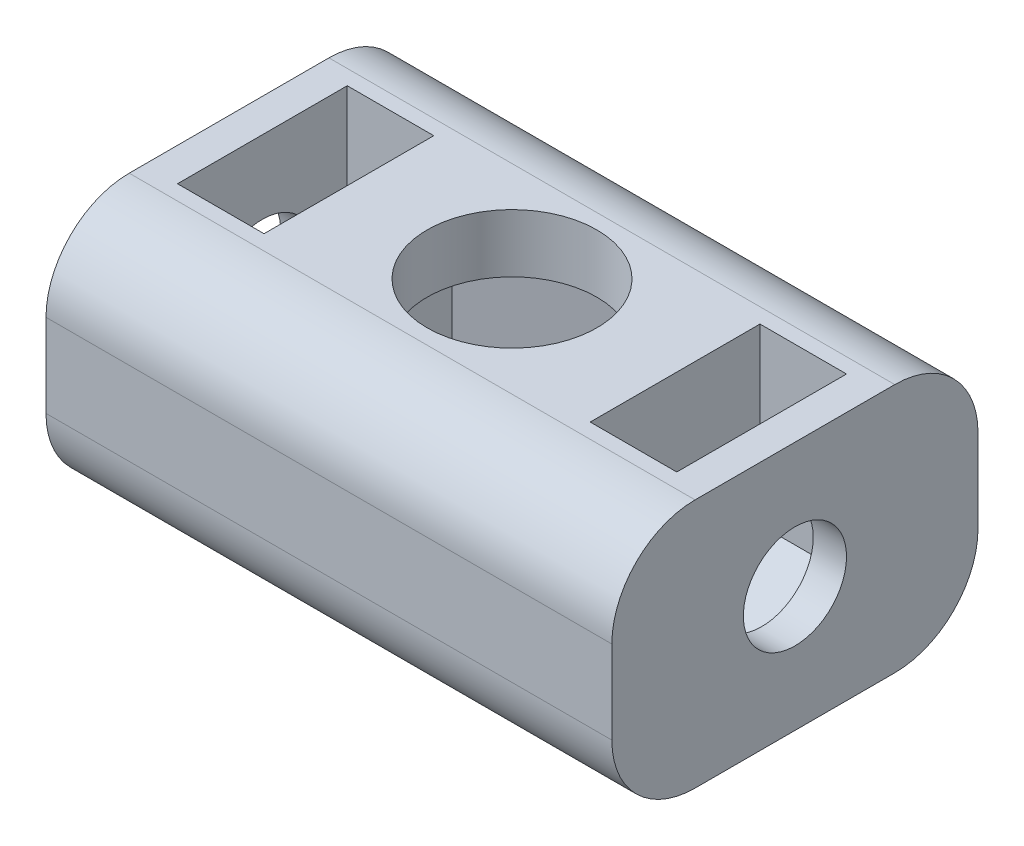
SolidWorks part; units mm, degrees
ref_plane "Alzado" through (0, 0, 0) normal (0, 0, 1) x (1, 0, 0)
ref_plane "Planta" through (0, 0, 0) normal (0, 1, 0) x (1, 0, 0)
ref_plane "Vista lateral" through (0, 0, 0) normal (1, 0, 0) x (0, 0, -1)
sketch "Croquis1" plane through (0, 0, 0) normal (0, 1, 0) x (1, 0, 0)
  line L0 (17, 22) -> (17, 0) construction
  line L1 (0, 0) -> (34, 0)
  line L2 (0, 0) -> (0, 22)
  line L3 (0, 22) -> (34, 22)
  line L4 (34, 0) -> (34, 22)
  circle A0 centre (17, 11) radius 5.1
  dimension "D3" = 10.2
  dimension "D1" = 34
  dimension "D2" = 22
extrude "Saliente-Extruir1" add sketch "Croquis1" along normal blind 15
ref_plane "Plano1" through (2, 0, 0) normal (-1, 0, 0) x (0, 0, 1)
sketch "Croquis2" plane through (2, 0, 0) normal (-1, 0, 0) x (0, 0, 1)
  line L0 (-11, 15) -> (-11, 0) construction
  line L1 (-22, 15) -> (0, 15) construction
  line L2 (-22, 0) -> (0, 0) construction
  line L3 (-16.1, 10.4445) -> (-16.1, 15)
  line L4 (-11, 1.611) -> (-5.9, 4.5555)
  line L5 (-5.9, 4.5555) -> (-5.9, 10.4445)
  line L6 (-5.9, 10.4445) -> (-11, 13.389) construction
  line L7 (-11, 13.389) -> (-16.1, 10.4445) construction
  line L8 (-16.1, 10.4445) -> (-16.1, 4.5555)
  line L9 (-16.1, 4.5555) -> (-11, 1.611)
  line L10 (-16.1, 15) -> (-5.9, 15)
  line L11 (-5.9, 15) -> (-5.9, 10.4445)
  circle A0 centre (-11, 7.5) radius 5.1 construction
  point P7 (-16.1, 7.5)
  point P15 (0, 0)
  point P20 (-19.6485, 15)
  dimension "D1" = 10.2
extrude "Cortar-Extruir1" cut sketch "Croquis2" against normal blind 5.2
ref_plane "Plano2" through (32, 0, 0) normal (1, 0, 0) x (0, 0, -1)
sketch "Croquis3" plane through (32, 0, 0) normal (1, 0, 0) x (0, 0, -1)
  line L0 (5.9, 15) -> (5.9, 0) construction
  line L1 (16.1, 0) -> (16.1, 15) construction
  line L2 (0, 15) -> (22, 15) construction
  line L3 (16.1, 4.5555) -> (11, 1.611) construction
  line L4 (11, 1.611) -> (5.9, 4.5555) construction
  line L5 (5.9, 15) -> (5.9, 4.5555)
  line L6 (16.1, 4.5555) -> (16.1, 15)
  line L7 (5.9, 15) -> (16.1, 15)
  line L8 (16.1, 4.5555) -> (11, 1.611)
  line L9 (11, 1.611) -> (5.9, 4.5555)
extrude "Cortar-Extruir2" cut sketch "Croquis3" against normal blind 5.2
ref_plane "Plano3" through (0, 7.5, 0) normal (0, 1, 0) x (1, 0, 0)
sketch "Croquis4" plane through (0, 7.5, 0) normal (0, 1, 0) x (1, 0, 0)
  line L0 (17, 20.815) -> (17, 22) construction
  line L1 (8.5, 6.0925) -> (17, 1.185)
  line L2 (17, 1.185) -> (25.5, 6.0925)
  line L3 (25.5, 6.0925) -> (25.5, 15.9075)
  line L4 (25.5, 15.9075) -> (17, 20.815)
  line L5 (17, 20.815) -> (8.5, 15.9075)
  line L6 (8.5, 15.9075) -> (8.5, 6.0925)
  line L7 (34, 22) -> (0, 22) construction
  circle A0 centre (17, 11) radius 8.5 construction
  point P1 (17, 2.8344)
  dimension "D1" = 17
extrude "Cortar-Extruir3" cut sketch "Croquis4" against normal blind 4 and the other way blind 4
sketch "Croquis5" plane through (34, 0, 0) normal (1, 0, 0) x (0, 0, -1)
  line L0 (11, 1.611) -> (11, 15) construction
  line L1 (0, 15) -> (22, 15) construction
  line L2 (0, 7.5) -> (22, 7.5) construction
  line L3 (0, 15) -> (0, 0) construction
  line L4 (22, 15) -> (22, 0) construction
  circle A0 centre (11, 7.5) radius 3.1
  dimension "D1" = 6.2
extrude "Cortar-Extruir4" cut sketch "Croquis5" against normal blind 4
sketch "Croquis6" plane through (0, 0, 0) normal (-1, 0, 0) x (0, 0, 1)
  circle A0 centre (-11, 7.5) radius 3.1 construction
  circle A1 centre (-11, 7.5) radius 3.1
extrude "Cortar-Extruir5" cut sketch "Croquis6" against normal blind 4
fillet "Redondeo1" radius 5 4 edges at (17, 0, 0) (17, 0, -22) (17, 15, 0) (17, 15, -22)
